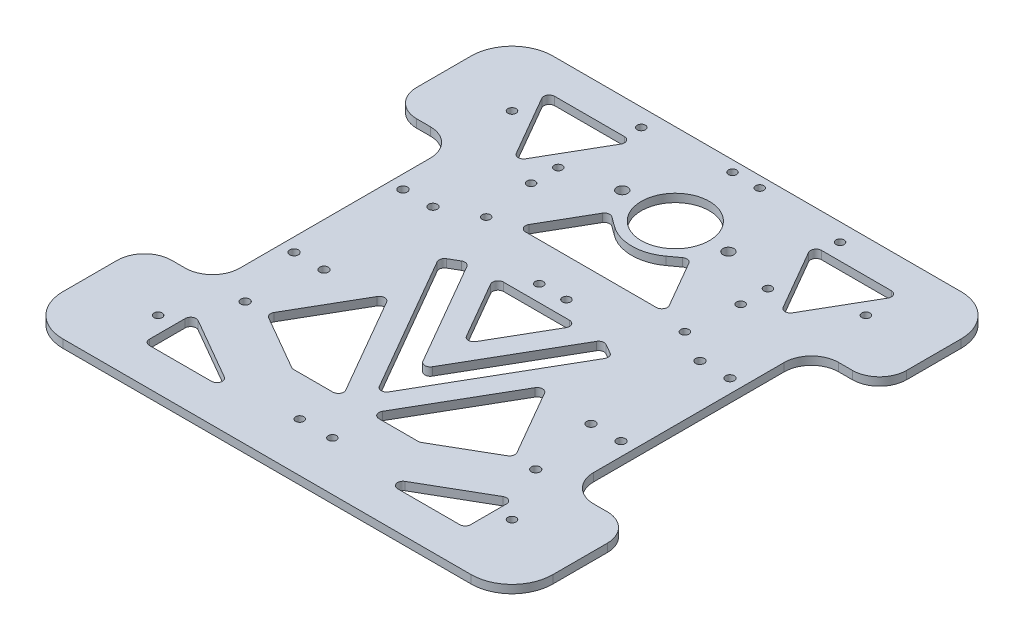
SolidWorks part; units mm, degrees
material "ABS"
ref_plane "Спереди" through (0, 0, 0) normal (0, 0, 1) x (1, 0, 0)
ref_plane "Сверху" through (0, 0, 0) normal (0, 1, 0) x (1, 0, 0)
ref_plane "Справа" through (0, 0, 0) normal (1, 0, 0) x (0, 0, -1)
sketch "Sketch1" plane through (0, 0, 0) normal (0, 1, 0) x (1, 0, 0)
  line L1 (-90, 90) -> (90, 90)
  line L2 (-90, 90) -> (-90, -90)
  line L3 (-90, -90) -> (90, -90)
  line L4 (90, 90) -> (90, -90)
  line L5 (-90, 90) -> (90, -90) construction
  line L6 (-90, -90) -> (90, 90) construction
  point P0 (0, 0)
  dimension "D1" = 180
  dimension "D2" = 180
extrude "Boss-Extrude1" add sketch "Sketch1" along normal blind 3
fillet "Fillet1" radius 15 4 edges at (-90, 1.5, -90) (90, 1.5, -90) (-90, 1.5, 90) (90, 1.5, 90)
sketch "Sketch2" plane through (0, 3, 0) normal (0, 1, 0) x (1, 0, 0)
  line L0 (0, 0) -> (-77.5, 0) construction
  line L1 (1.65, 0) -> (-1.65, 0) construction
  line L2 (-90, 75) -> (-90, -75) construction
  line L3 (-90, 45) -> (-65, 45)
  line L4 (-90, 45) -> (-90, -45)
  line L5 (-90, -45) -> (-65, -45)
  line L6 (-65, 45) -> (-65, -45)
  line L7 (-90, 45) -> (-65, -45) construction
  line L8 (-90, -45) -> (-65, 45) construction
  line L9 (0, 0) -> (0, 45) construction
  line L10 (90, -45) -> (65, 45) construction
  line L11 (90, 45) -> (65, -45) construction
  line L12 (65, 45) -> (65, -45)
  line L13 (90, -45) -> (65, -45)
  line L14 (90, 45) -> (90, -45)
  line L15 (90, 45) -> (65, 45)
  circle A0 centre (-60.05, 20) radius 1.6
  circle A1 centre (-49.05, 20) radius 1.6
  circle A2 centre (-60.05, -20) radius 1.6
  circle A3 centre (-49.05, -20) radius 1.6
  circle A4 centre (49.05, 20) radius 1.6
  circle A5 centre (60.05, 20) radius 1.6
  circle A6 centre (49.05, -20) radius 1.6
  circle A7 centre (60.05, -20) radius 1.6
  circle A8 centre (-60.05, -20) radius 1.6 construction
  circle A14 centre (-60.05, 20) radius 1.6 construction
  circle A15 centre (-49.05, 20) radius 1.6 construction
  circle A16 centre (-49.05, -20) radius 1.6 construction
  circle A17 centre (49.05, -20) radius 1.6 construction
  circle A18 centre (60.05, -20) radius 1.6 construction
  circle A19 centre (49.05, 20) radius 1.6 construction
  circle A20 centre (60.05, 20) radius 1.6 construction
  dimension "D1" = 25
  dimension "D2" = 90
extrude "Cut-Extrude2" cut sketch "Sketch2" against normal through all
fillet "Fillet2" radius 10 8 edges at (-65, 1.5, 45) (-65, 1.5, -45) (65, 1.5, -45) (65, 1.5, 45) (90, 1.5, -45) (90, 1.5, 45) (-90, 1.5, 45) (-90, 1.5, -45)
hole_wizard "Диаметр отверстия Ø3.0 (3)1" positions "Эскиз2" profile "Эскиз1" hole size "Ø3.0" standard "Ansi Metric" end condition up to next
sketch "Эскиз2" plane through (0, 3, 0) normal (0, 1, 0) x (1, 0, 0)
  line L7 (-65, -65) -> (-65, 65) construction
  line L9 (65, 65) -> (65, -65) construction
  line L11 (-90, 65) -> (-65, 65) construction
  line L12 (-90, 75) -> (-90, 55) construction
  line L13 (-65, 65) -> (65, 65) construction
  line L14 (65, 65) -> (90, 65) construction
  line L15 (90, 55) -> (90, 75) construction
  line L17 (90, -65) -> (65, -65) construction
  line L18 (90, -75) -> (90, -55) construction
  line L19 (65, -65) -> (-65, -65) construction
  line L20 (-65, -65) -> (-90, -65) construction
  line L21 (-90, -55) -> (-90, -75) construction
  line L22 (-65, 65) -> (-65, 90) construction
  line L23 (75, 90) -> (-75, 90) construction
  point P15 (-65, -65)
  point P16 (-65, 65)
  point P19 (65, 65)
  point P20 (65, -65)
sketch "Эскиз1" plane through (-65, 3, 65) normal (1, 0, 0) x (0, 0, 1)
  line L0 (0, 0) -> (0, 3)
  line L1 (0, 3) -> (1.5, 3)
  line L2 (1.5, 3) -> (1.5, 0)
  line L5 (1.5, 0) -> (0, 0)
  line L11 (0, -6.35) -> (0, 107.95) construction
  dimension "Диаметр сквозного отверстия" = 3
  dimension "Глубина сквозного отверстия" = 3
hole_wizard "Диаметр отверстия Ø3.0 (3)2" positions "Эскиз4" profile "Эскиз3" hole size "Ø3.0" standard "Ansi Metric" end condition up to next
sketch "Эскиз4" plane through (0, 3, 0) normal (0, 1, 0) x (1, 0, 0)
  line L0 (90, 65) -> (38.5, 65) construction
  line L1 (90, 55) -> (90, 75) construction
  line L2 (38.5, 65) -> (-38.5, 65) construction
  line L3 (-38.5, 65) -> (-90, 65) construction
  line L4 (-90, 75) -> (-90, 55) construction
  line L12 (-38.5, 15) -> (-5, 15) construction
  line L13 (-5, 15) -> (5, 15) construction
  line L14 (5, 15) -> (38.5, 15) construction
  line L16 (38.5, 86) -> (5, 86) construction
  line L17 (5, 86) -> (-5, 86) construction
  line L18 (-5, 86) -> (-38.5, 86) construction
  line L20 (38.5, 15) -> (38.5, 45.5) construction
  line L21 (38.5, 45.5) -> (38.5, 55.5) construction
  line L22 (38.5, 55.5) -> (38.5, 86) construction
  line L24 (-38.5, 86) -> (-38.5, 55.5) construction
  line L25 (-38.5, 55.5) -> (-38.5, 45.5) construction
  line L26 (-38.5, 45.5) -> (-38.5, 15) construction
  line L28 (75, 90) -> (-75, 90) construction
  point P63 (-5, 15)
  point P66 (-38.5, 45.5)
  point P69 (-38.5, 55.5)
  point P72 (5, 15)
  point P75 (38.5, 45.5)
  point P78 (38.5, 55.5)
  point P81 (5, 86)
  point P84 (-5, 86)
  dimension "D1" = 10
  dimension "D2" = 71
  dimension "D3" = 77
  dimension "D4" = 4
sketch "Эскиз3" plane through (-5, 3, -15) normal (1, 0, 0) x (0, 0, 1)
  line L0 (0, 0) -> (0, 3)
  line L1 (0, 3) -> (1.5, 3)
  line L2 (1.5, 3) -> (1.5, 0)
  line L5 (1.5, 0) -> (0, 0)
  line L11 (0, -6.35) -> (0, 107.95) construction
  dimension "Диаметр сквозного отверстия" = 3
  dimension "Глубина сквозного отверстия" = 3
hole_wizard "Диаметр отверстия Ø4.0 (4)1" positions "Эскиз6" profile "Эскиз5" hole size "Ø4.0" standard "Ansi Metric" end condition up to next
sketch "Эскиз6" plane through (0, 3, 0) normal (0, 1, 0) x (1, 0, 0)
  line L0 (0, 90) -> (0, 60) construction
  line L1 (75, 90) -> (-75, 90) construction
  line L2 (0, 60) -> (0, -90) construction
  line L3 (-75, -90) -> (75, -90) construction
  line L5 (-19.5, 60) -> (19.5, 60) construction
  point P1 (-19.5, 60)
  point P20 (19.5, 60)
  dimension "D1" = 39
  dimension "D2" = 30
sketch "Эскиз5" plane through (-19.5, 3, -60) normal (1, 0, 0) x (0, 0, 1)
  line L0 (0, 0) -> (0, 3)
  line L1 (0, 3) -> (2, 3)
  line L2 (2, 3) -> (2, 0)
  line L5 (2, 0) -> (0, 0)
  line L11 (0, -6.35) -> (0, 107.95) construction
  dimension "Диаметр сквозного отверстия" = 4
  dimension "Глубина сквозного отверстия" = 3
sketch "Sketch3" plane through (0, 3, 0) normal (0, 1, 0) x (1, 0, 0)
  line L0 (0, -90) -> (0, -72) construction
  line L1 (-75, -90) -> (75, -90) construction
  line L2 (0, -72) -> (-6, -72) construction
  circle A0 centre (-6, -72) radius 1.5
  circle A1 centre (6, -72) radius 1.5
  circle A2 centre (53.3716, -44.65) radius 1.6
  circle A3 centre (-53.3716, -44.65) radius 1.6
  arc A4 (-52.7899, -46.1405) -> (-54.9533, -44.8915) centre (-53.3716, -44.65) ccw construction
  arc A5 (54.9533, -44.8915) -> (52.7899, -46.1405) centre (53.3716, -44.65) ccw construction
  dimension "D2" = 3
  dimension "D1" = 18
  dimension "D3" = 12
extrude "Cut-Extrude3" cut sketch "Sketch3" against normal through all
sketch "Sketch4" plane through (0, 3, 0) normal (0, 1, 0) x (1, 0, 0)
  circle A0 centre (-36, 83.5) radius 1.5
  circle A1 centre (37, 83.5) radius 1.5
  circle A2 centre (37, 26.5) radius 1.5
  circle A3 centre (-36, 26.5) radius 1.5
  circle A4 centre (-36, 26.5) radius 1.5 construction
  circle A5 centre (37, 26.5) radius 1.5 construction
  circle A7 centre (37, 83.5) radius 1.5 construction
  circle A8 centre (-36, 83.5) radius 1.5 construction
extrude "Cut-Extrude4" cut sketch "Sketch4" against normal through all
sketch "Sketch5" plane through (0, 3, 0) normal (0, 1, 0) x (1, 0, 0)
  line L0 (0, 0) -> (0, -90) construction
  line L1 (-75, -90) -> (75, -90) construction
  line L2 (31.7543, 5) -> (0, -50)
  line L3 (0, -18) -> (15.5885, 9)
  line L4 (15.5885, 9) -> (-15.5885, 9)
  line L5 (-15.5885, 9) -> (0, -18)
  line L6 (31.7543, 5) -> (24.8261, 9)
  line L7 (6.9282, -38) -> (0, -34) construction
  line L8 (24.8261, 9) -> (0, -34)
  line L9 (31.7543, 5) -> (0, -34) construction
  line L10 (6.9282, -38) -> (24.8261, 9) construction
  line L11 (15.5885, 9) -> (24.8261, 9) construction
  line L12 (-31.7543, 5) -> (0, -50)
  line L13 (-24.8261, 9) -> (0, -34)
  line L14 (-31.7543, 5) -> (-24.8261, 9)
  line L15 (-5, -57.3397) -> (-23.3923, -57.3397)
  line L16 (-29, -15.7705) -> (-5, -57.3397)
  line L17 (29, -15.7705) -> (5, -57.3397)
  line L18 (5, -57.3397) -> (23.3923, -57.3397)
  line L19 (45.5981, -44.5192) -> (29, -15.7705)
  line L20 (-45.5981, -44.5192) -> (-29, -15.7705)
  line L21 (0, 0) -> (0, 44.8771) construction
  line L22 (-14.8005, 50.9961) -> (-27.5, 29)
  line L23 (-59, -57.5662) -> (-26.7254, -76.2)
  line L24 (-27.5, 29) -> (27.5, 29)
  line L25 (27.5, 29) -> (14.8005, 50.9961)
  line L26 (-26.7254, -76.2) -> (-59, -76.2)
  line L27 (-14.8005, 50.9961) -> (-9.4359, 47.0786)
  line L28 (-9.4359, 47.0786) -> (-22.1538, 56.3658) construction
  line L29 (9.4359, 47.0786) -> (14.8005, 50.9961)
  line L30 (-45.5981, -44.5192) -> (-23.3923, -57.3397)
  line L31 (-0.839, -70.3609) -> (-54.5326, -39.3609) construction
  line L32 (45.5981, -44.5192) -> (23.3923, -57.3397)
  line L33 (54.5326, -39.3609) -> (0.839, -70.3609) construction
  line L34 (23.3923, -57.3397) -> (53, -57.3397) construction
  line L35 (45.5981, -44.5192) -> (53, -57.3397) construction
  line L37 (-49.0076, 49.3003) -> (-32.7265, 77.5)
  line L38 (-32.7265, 77.5) -> (-65.2887, 77.5)
  line L39 (-65.2887, 77.5) -> (-49.0076, 49.3003)
  line L40 (32.7265, 77.5) -> (65.2887, 77.5)
  line L41 (65.2887, 77.5) -> (49.0076, 49.3003)
  line L42 (49.0076, 49.3003) -> (32.7265, 77.5)
  line L43 (0, 76.6314) -> (-0.367, 75.9958) [skipped]
  line L44 (-59, -76.2) -> (-59, -57.5662)
  line L45 (-61.0326, -50.6192) -> (-7.339, -81.6192) construction
  line L46 (-22.85, -78.2) -> (-32.5, -78.2) construction
  line L47 (59, -57.5662) -> (26.7254, -76.2)
  line L48 (59, -76.2) -> (59, -57.5662)
  line L49 (26.7254, -76.2) -> (59, -76.2)
  circle A0 centre (0, 0) radius 9 construction
  circle A1 centre (-5, 15) radius 1.5 construction
  circle A2 centre (29, -43.4833) radius 13.8564 construction
  circle A3 centre (0, 44.8771) radius 15.8771 construction
  circle A4 centre (-49.0076, 68.1001) radius 9.3999 construction
  circle A5 centre (-38.5, 55.5) radius 1.5 construction
  circle A6 centre (0, 60) radius 12.5
  arc A7 (-9.4359, 47.0786) -> (9.4359, 47.0786) centre (0, 60) ccw
  circle A8 centre (-36, 83.5) radius 1.5 construction
  circle A9 centre (0, 60) radius 14 construction
  point P12 (15.8771, -14.5)
  point P51 (23.3923, -57.3397)
  dimension "D12" = 1.5
  dimension "D1" = 6
  dimension "D2" = 8
  dimension "D3" = 8
  dimension "D4" = 8
  dimension "D5" = 5
  dimension "D6" = 48
  dimension "D7" = 20
  dimension "D8" = 55
  dimension "D9" = 6
  dimension "D10" = 6
  dimension "D11" = 6
  dimension "D13" = 6
  dimension "D14" = 5
  dimension "D15" = 2
extrude "Cut-Extrude5" cut sketch "Sketch5" against normal through all
fillet "Fillet3" radius 2 33 edges at (-5, 1.5, 57.3397) (-23.3923, 1.5, 57.3397) (-45.5981, 1.5, 44.5192) (-29, 1.5, 15.7705) (45.5981, 1.5, 44.5192) (29, 1.5, 15.7705) (23.3923, 1.5, 57.3397) (5, 1.5, 57.3397) (0, 1.5, 34) (0, 1.5, 50) (-31.7543, 1.5, -5) (-24.8261, 1.5, -9) (31.7543, 1.5, -5) (24.8261, 1.5, -9) (0, 1.5, 18) (15.5885, 1.5, -9) (-15.5885, 1.5, -9) (-27.5, 1.5, -29) (27.5, 1.5, -29) (14.8005, 1.5, -50.9961) (-14.8005, 1.5, -50.9961) (49.0076, 1.5, -49.3003) (65.2887, 1.5, -77.5) (32.7265, 1.5, -77.5) (-65.2887, 1.5, -77.5) (-49.0076, 1.5, -49.3003) (-32.7265, 1.5, -77.5) (-59, 1.5, 57.5662) (-59, 1.5, 76.2) (-26.7254, 1.5, 76.2) (26.7254, 1.5, 76.2) (59, 1.5, 57.5662) (59, 1.5, 76.2)
